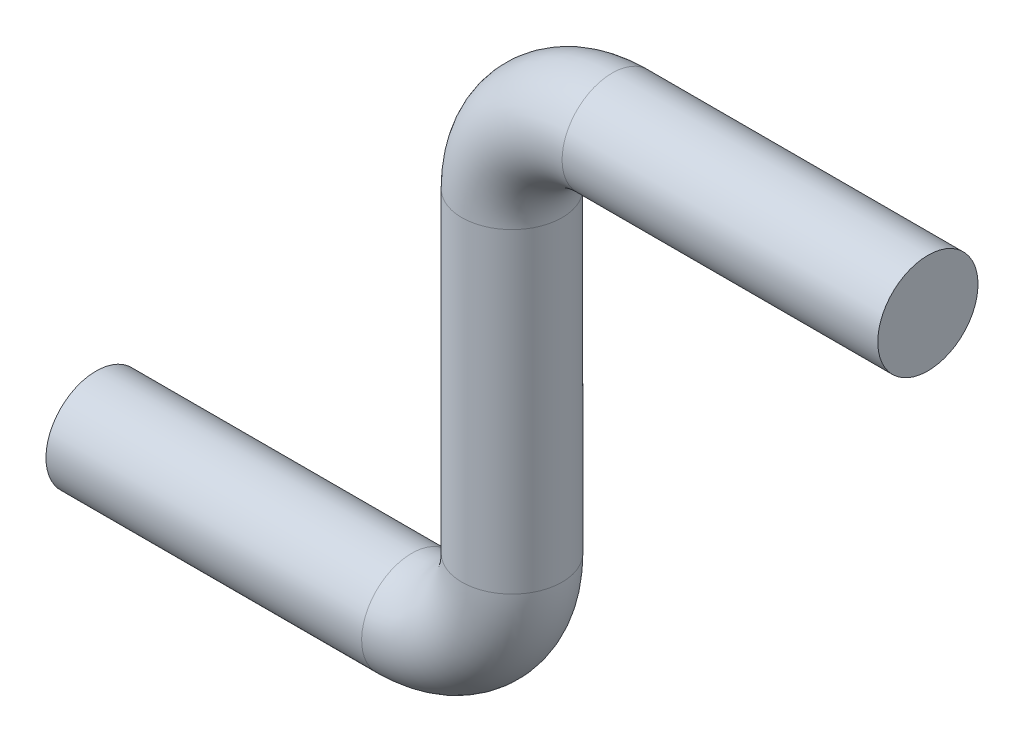
SolidWorks part; units mm, degrees
material "Copper"
ref_plane "Front Plane" through (0, 0, 0) normal (0, 0, 1) x (1, 0, 0)
ref_plane "Top Plane" through (0, 0, 0) normal (0, 1, 0) x (1, 0, 0)
ref_plane "Right Plane" through (0, 0, 0) normal (1, 0, 0) x (0, 0, -1)
sketch "Sketch1" plane through (0, 0, 0) normal (0, 0, 1) x (1, 0, 0)
  line L0 (0, 0) -> (5, 0)
  line L1 (6.5875, 1.5875) -> (6.5875, 6.5875)
  line L2 (8.175, 8.175) -> (13.175, 8.175)
  arc A0 (5, 0) -> (6.5875, 1.5875) centre (5, 1.5875) ccw
  arc A1 (6.5875, 6.5875) -> (8.175, 8.175) centre (8.175, 6.5875) cw
  dimension "D4" = 1.5875
  dimension "D5" = 1.5875
  dimension "D1" = 5
  dimension "D2" = 5
  dimension "D3" = 5
sketch "Sketch2" plane through (0, 0, 0) normal (1, 0, 0) x (0, 0, -1)
  circle A0 centre (0, 0) radius 0.7937
  dimension "D1" = 1.5875
sweep "Sweep1" add profiles "Sketch2" path "Sketch1"
